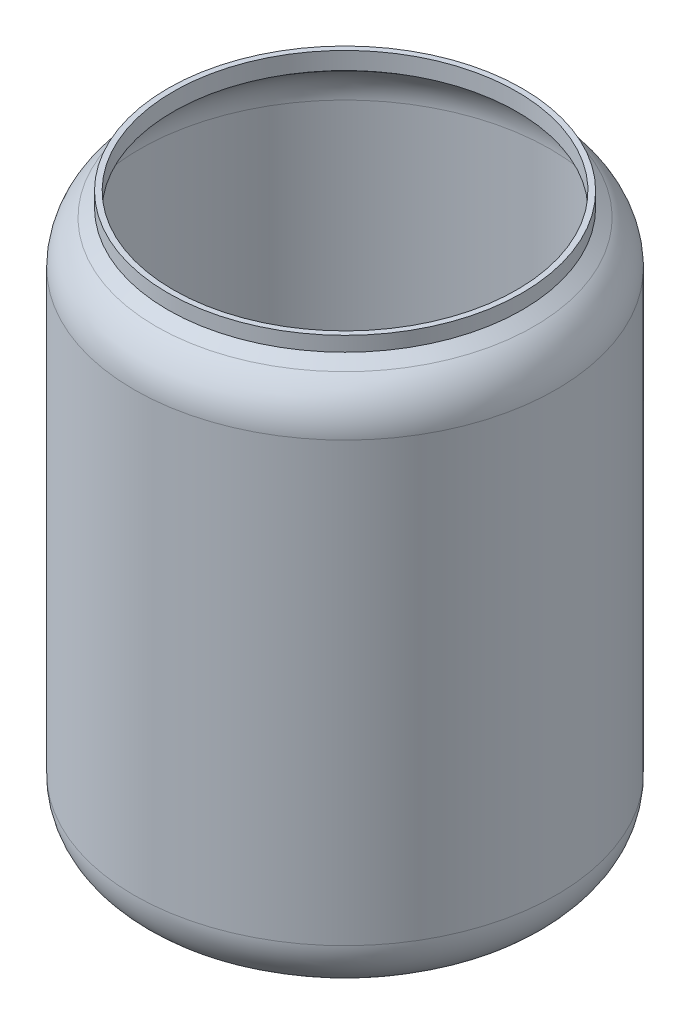
SolidWorks part; units mm, degrees
material "Acrylic (Medium-high impact)"
ref_plane "Front Plane" through (0, 0, 0) normal (0, 0, 1) x (1, 0, 0)
ref_plane "Top Plane" through (0, 0, 0) normal (0, 1, 0) x (1, 0, 0)
ref_plane "Right Plane" through (0, 0, 0) normal (1, 0, 0) x (0, 0, -1)
sketch "Sketch1" plane through (0, 0, 0) normal (0, 0, 1) x (1, 0, 0)
  line L0 (0, 85.7639) -> (0, 0) construction
  line L1 (39, 90.9312) -> (39, 10)
  line L2 (29, 0) -> (0, 0)
  line L3 (32.7527, 103.2885) -> (32.7527, 100.5792)
  line L4 (32.7527, 100.5792) -> (34.9118, 98.9966)
  line L5 (31.7527, 103.2885) -> (31.7527, 100.0723)
  line L6 (31.7527, 100.0723) -> (34.3206, 98.19)
  line L7 (38, 90.9312) -> (38, 10)
  line L8 (29, 1) -> (0, 1)
  line L9 (0, 1) -> (0, 0)
  line L10 (31.7527, 103.2885) -> (32.7527, 103.2885)
  arc A0 (39, 90.9312) -> (34.9118, 98.9966) centre (29, 90.9312) ccw
  arc A1 (39, 10) -> (29, 0) centre (29, 10) cw
  arc A2 (38, 90.9312) -> (34.3206, 98.19) centre (29, 90.9312) ccw
  arc A3 (38, 10) -> (29, 1) centre (29, 10) cw
  point P9 (39, 96)
  point P12 (39, 0)
  dimension "D3" = 10
  dimension "D4" = 10
  dimension "D1" = 39
  dimension "D2" = 96
  dimension "D5" = 1
revolve "Revolve1" add sketch "Sketch1" angle 360 about L0
